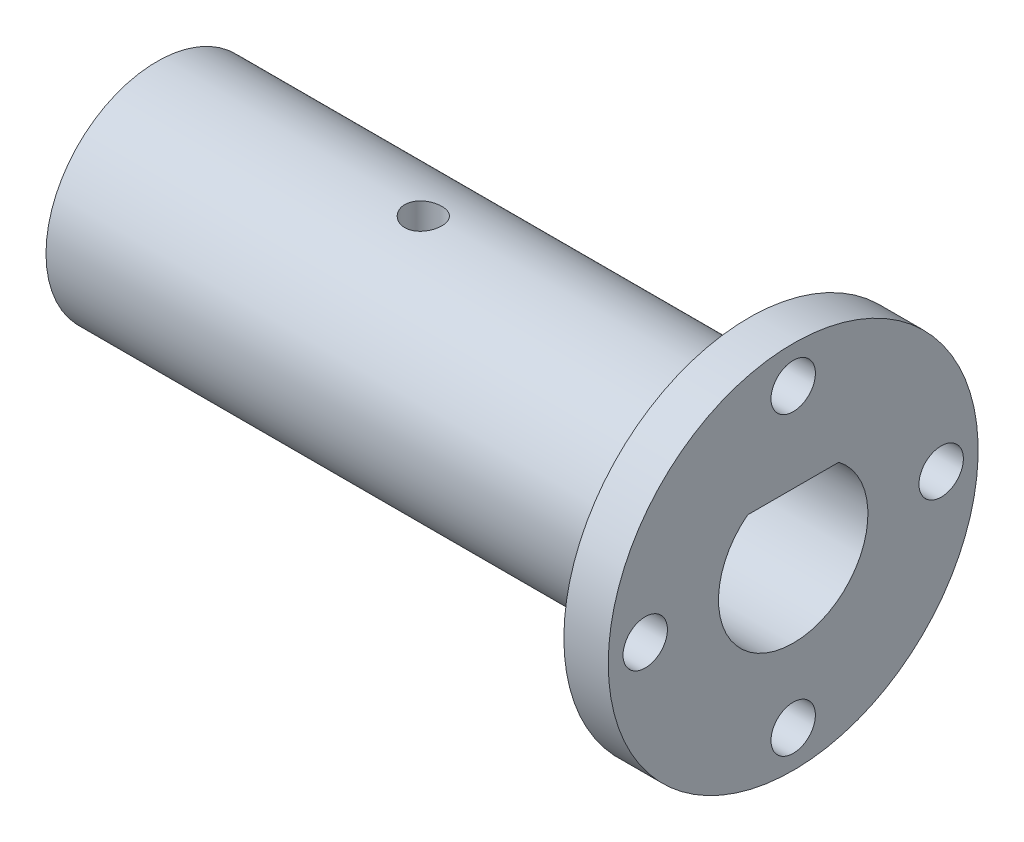
SolidWorks part; units mm, degrees
ref_plane "前视基准面" through (0, 0, 0) normal (0, 0, 1) x (1, 0, 0)
ref_plane "上视基准面" through (0, 0, 0) normal (0, 1, 0) x (1, 0, 0)
ref_plane "右视基准面" through (0, 0, 0) normal (1, 0, 0) x (0, 0, -1)
ref_plane "基准面1" through (0, 0, 0) normal (0, 0, -1) x (-1, 0, 0)
sketch "草图1" plane through (0, 0, 0) normal (0, 0, -1) x (-1, 0, 0)
  line L0 (-43, 12.5) -> (-43, 0)
  line L1 (-43, 0) -> (-40, 0)
  line L2 (-40, 0) -> (-40, 12.5)
  line L3 (-40, 12.5) -> (-43, 12.5)
  line L4 (-43, 0) -> (-40, 0) construction
revolve "旋转1" add sketch "草图1" angle 360 about L4
sketch "草图2" plane through (40, 0, 0) normal (-1, 0, 0) x (0, 0, 1)
  circle A0 centre (0, 0) radius 7.5
extrude "凸台-拉伸1" add sketch "草图2" along normal blind 40
sketch "草图3" plane through (0, 0, 0) normal (-1, 0, 0) x (0, 0, 1)
  line L0 (3.0826, 4) -> (-3.0826, 4)
  arc A0 (-3.0826, 4) -> (3.0826, 4) centre (0, 0) ccw
extrude "切除-拉伸1" cut sketch "草图3" against normal through all
hole_wizard "Ø3.0 (3) 直径孔3" positions "草图8" profile "草图7" hole size "Ø3.0" standard "ANSI Metric" end condition through all
sketch "草图8" plane through (40, 0, 0) normal (-1, 0, 0) x (0, 0, 1)
  point P0 (10, 0)
  point P1 (0, -10)
  point P2 (-10, 0)
  point P3 (0, 10)
sketch "草图7" plane through (40, 0, 10) normal (0, 1, 0) x (0, 0, 1)
  line L0 (0, 0) -> (0, 3)
  line L1 (0, 3) -> (1.5, 3)
  line L2 (1.5, 3) -> (1.5, 0)
  line L5 (1.5, 0) -> (0, 0)
  line L11 (0, -6.35) -> (0, 107.95) construction
  dimension "通孔孔直径" = 3
  dimension "通孔孔深度" = 3
sketch "草图9" plane through (0, 4, 0) normal (0, -1, 0) x (1, 0, 0)
  line L0 (0, 7.5) -> (0, -7.5) construction
  circle A0 centre (18, 0) radius 1.25
  dimension "D2" = 2.5
  dimension "D1" = 18
extrude "切除-拉伸2" cut sketch "草图9" against normal blind 10
